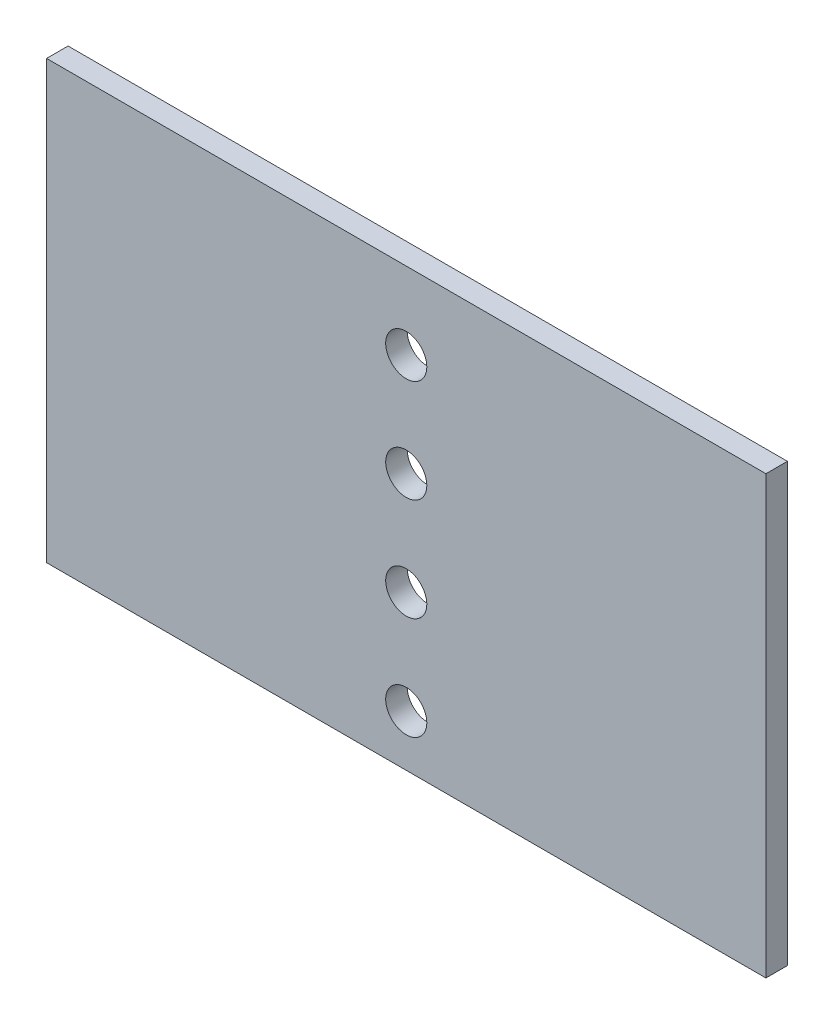
SolidWorks part; units mm, degrees
ref_plane "Front Plane" through (0, 0, 0) normal (0, 0, 1) x (1, 0, 0)
ref_plane "Top Plane" through (0, 0, 0) normal (0, 1, 0) x (1, 0, 0)
ref_plane "Right Plane" through (0, 0, 0) normal (1, 0, 0) x (0, 0, -1)
sketch "Sketch1" plane through (0, 0, 0) normal (0, 0, 1) x (1, 0, 0)
  line L1 (0, 0) -> (88.9, 0)
  line L2 (0, 0) -> (0, 53.975)
  line L3 (0, 53.975) -> (88.9, 53.975)
  line L4 (88.9, 0) -> (88.9, 53.975)
  dimension "D1" = 88.9
  dimension "D2" = 53.975
extrude "Boss-Extrude1" add sketch "Sketch1" along normal blind 2.6568
sketch "Sketch2" plane through (0, 0, 2.6568) normal (0, 0, 1) x (1, 0, 0)
  line L0 (44.45, 0) -> (44.45, 6.35) construction
  line L1 (0, 0) -> (88.9, 0) construction
  line L2 (44.45, 6.35) -> (44.45, 19.05) construction
  line L3 (44.45, 19.05) -> (44.45, 31.75) construction
  line L4 (88.9, 53.975) -> (0, 53.975) construction
  circle A0 centre (44.45, 6.35) radius 2.54
  circle A1 centre (44.45, 19.05) radius 2.54
  circle A2 centre (44.45, 31.75) radius 2.54
  circle A3 centre (44.45, 44.45) radius 2.54
  dimension "D1" = 5.08
  dimension "D5" = 12.7
  dimension "D2" = 12.7
  dimension "D3" = 6.35
  dimension "D4" = 22.225
extrude "Cut-Extrude1" cut sketch "Sketch2" against normal through all
